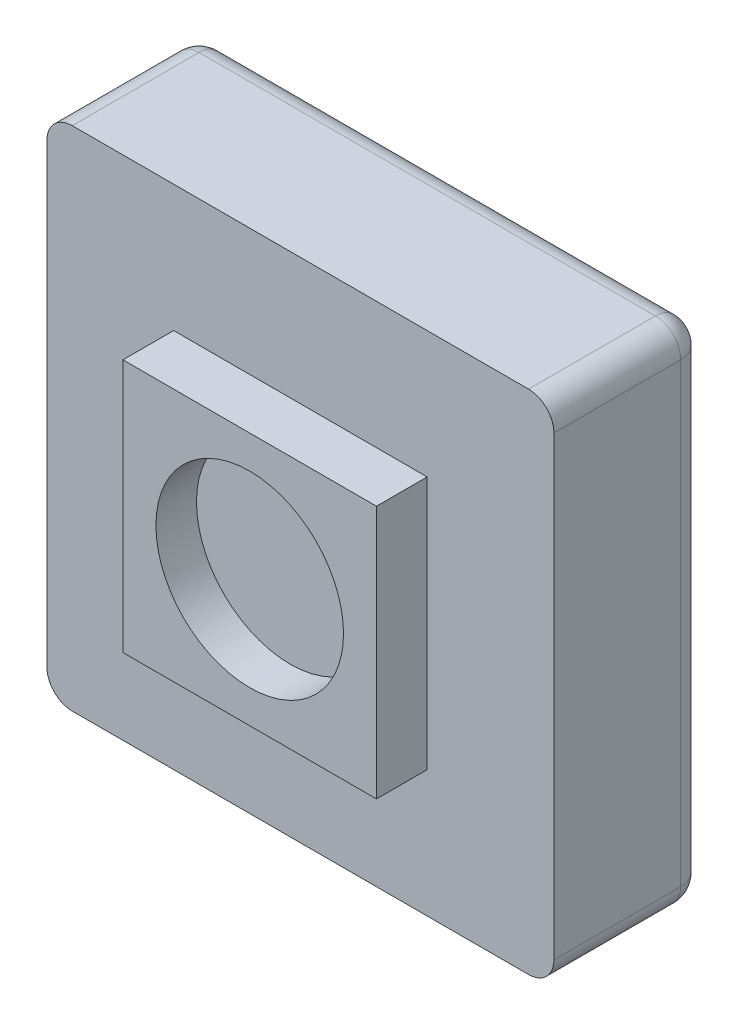
SolidWorks part; units mm, degrees
ref_plane "Front Plane" through (0, 0, 0) normal (0, 0, 1) x (1, 0, 0)
ref_plane "Top Plane" through (0, 0, 0) normal (0, 1, 0) x (1, 0, 0)
ref_plane "Right Plane" through (0, 0, 0) normal (1, 0, 0) x (0, 0, -1)
sketch "Sketch1" plane through (0, 0, 0) normal (0, 0, 1) x (1, 0, 0)
  line L1 (-5, 5) -> (5, 5)
  line L2 (-5, 5) -> (-5, -5)
  line L3 (-5, -5) -> (5, -5)
  line L4 (5, 5) -> (5, -5)
  line L5 (-5, 5) -> (5, -5) construction
  line L6 (-5, -5) -> (5, 5) construction
  point P0 (0, 0)
  dimension "D1" = 10
  dimension "D2" = 10
extrude "Boss-Extrude1" add sketch "Sketch1" along normal blind 3
sketch "Sketch2" plane through (0, 0, 3) normal (0, 0, 1) x (1, 0, 0)
  line L1 (-2.5, 2.5) -> (2.5, 2.5)
  line L2 (-2.5, 2.5) -> (-2.5, -2.5)
  line L3 (-2.5, -2.5) -> (2.5, -2.5)
  line L4 (2.5, 2.5) -> (2.5, -2.5)
  line L5 (-2.5, 2.5) -> (2.5, -2.5) construction
  line L6 (-2.5, -2.5) -> (2.5, 2.5) construction
  point P0 (0, 0)
  dimension "D1" = 5
  dimension "D2" = 5
extrude "Boss-Extrude2" add sketch "Sketch2" along normal blind 1
sketch "Sketch3" plane through (0, 0, 4) normal (0, 0, 1) x (1, 0, 0)
  circle A0 centre (0, 0) radius 1.85
  dimension "D1" = 3.7
extrude "Cut-Extrude1" cut sketch "Sketch3" against normal blind 0.8
fillet "Fillet1" radius 0.5 4 edges at (-5, -5, 1.5) (-5, 5, 1.5) (5, 5, 1.5) (5, -5, 1.5)
fillet "Fillet2" radius 0.5 8 edges at (4.8536, -4.8536, 0) (5, 0, 0) (4.8536, 4.8536, 0) (0, 5, 0) (-4.8536, 4.8536, 0) (-5, 0, 0) (-4.8536, -4.8536, 0) (0, -5, 0)
